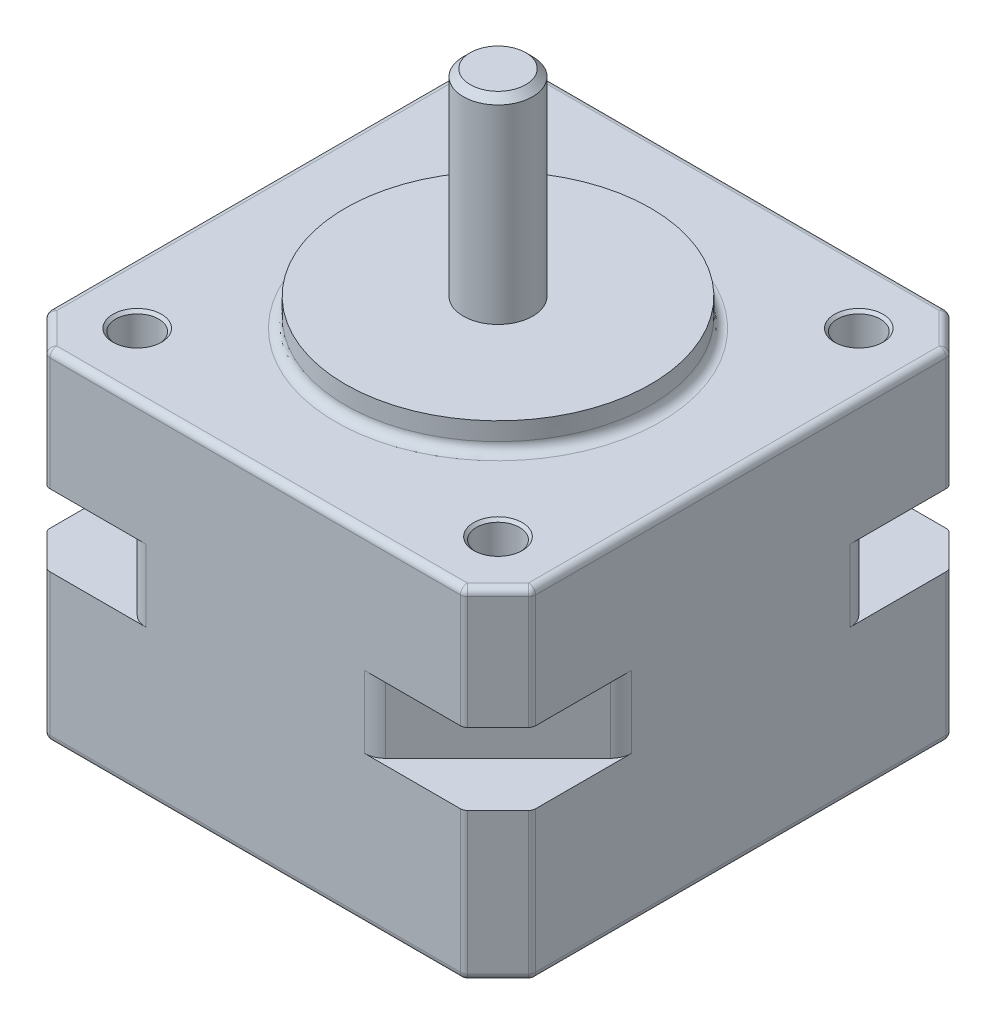
SolidWorks part; units mm, degrees
ref_plane "Front Plane" through (0, 0, 0) normal (0, 0, 1) x (1, 0, 0)
ref_plane "Top Plane" through (0, 0, 0) normal (0, 1, 0) x (1, 0, 0)
ref_plane "Right Plane" through (0, 0, 0) normal (1, 0, 0) x (0, 0, -1)
sketch "Sketch1" plane through (0, 0, 0) normal (0, 1, 0) x (1, 0, 0)
  line L0 (-35, 32.5) -> (-32.5, 35)
  line L1 (-2.5, 0) -> (-32.5, 0)
  line L2 (0, 2.5) -> (0, 32.5)
  line L3 (-2.5, 35) -> (-32.5, 35)
  line L4 (-35, 2.5) -> (-35, 6.85)
  line L5 (0, 32.5) -> (-2.5, 35)
  line L6 (-2.5, 0) -> (0, 2.5)
  line L7 (-32.5, 0) -> (-35, 2.5)
  line L8 (-17.5, 35) -> (-17.5, 0) construction
  line L9 (-42, 21) -> (0, 21) construction
  line L10 (-35, 28.15) -> (-36.65, 28.15)
  line L11 (-36.65, 28.15) -> (-36.65, 6.85)
  line L12 (-36.65, 6.85) -> (-35, 6.85)
  line L13 (-35, 28.15) -> (-35, 32.5)
  circle A0 centre (-17.5, 17.5) radius 4.5
  point P0 (0, 0)
  point P1 (-35, 35)
  point P2 (0, 35)
  point P3 (-35, 0)
  dimension "D11" = 9
  dimension "D1" = 35
  dimension "D2" = 35
  dimension "D3" = 2.5
  dimension "D4" = 45
  dimension "D5" = 2.5
  dimension "D6" = 45
  dimension "D7" = 2.5
  dimension "D8" = 45
  dimension "D9" = 2.5
  dimension "D10" = 45
  dimension "D12" = 1.65
  dimension "D13" = 21.3
extrude "Boss-Extrude1" add sketch "Sketch1" along normal blind 10.7
sketch "Sketch2" plane through (0, 10.7, 0) normal (0, 1, 0) x (1, 0, 0)
  line L1 (-26, 35) -> (-9, 35)
  line L2 (0, 26) -> (0, 9)
  line L3 (-9, 0) -> (-26, 0)
  line L5 (-35, 26) -> (-35, 9)
  line L6 (-26, 35) -> (-35, 26)
  line L7 (-9, 35) -> (0, 26)
  line L8 (0, 9) -> (-9, 0)
  line L9 (-26, 0) -> (-35, 9)
  line L10 (-2.5, 35) -> (-32.5, 35) construction
  point P1 (-35, 35)
  point P5 (0, 35)
  point P6 (0, 0)
  point P8 (-35, 0)
  dimension "D1" = 9
  dimension "D2" = 45
  dimension "D3" = 9
  dimension "D4" = 45
  dimension "D5" = 9
  dimension "D6" = 45
  dimension "D7" = 9
  dimension "D8" = 45
  dimension "D9" = 35
extrude "Boss-Extrude2" add sketch "Sketch2" along normal blind 5.18
sketch "Sketch3" plane through (0, 15.88, 0) normal (0, 1, 0) x (1, 0, 0)
  line L0 (-35, 2.5) -> (-35, 32.5)
  line L1 (-35, 32.5) -> (-32.5, 35)
  line L2 (-32.5, 35) -> (-2.5, 35)
  line L3 (-2.5, 35) -> (0, 32.5)
  line L4 (0, 32.5) -> (0, 2.5)
  line L5 (0, 2.5) -> (-2.5, 0)
  line L6 (-2.5, 0) -> (-32.5, 0)
  line L7 (-32.5, 0) -> (-35, 2.5)
extrude "Boss-Extrude3" add sketch "Sketch3" along normal blind 8.66 contours L1 L2 L3 L4 L5 L6 L7 L0
sketch "Sketch5" plane through (0, 24.54, 0) normal (0, 1, 0) x (1, 0, 0)
  line L0 (-30.5, 4.5) -> (-4.5, 4.5) construction
  line L1 (-4.5, 4.5) -> (-4.5, 30.5) construction
  line L2 (-4.5, 30.5) -> (-30.5, 30.5) construction
  line L3 (-17.5, 4.5) -> (-17.5, -1.0949) construction
  line L4 (-4.5, 17.5) -> (0, 17.5) construction
  line L6 (-35, 2.5) -> (-35, 32.5) construction
  circle A0 centre (-30.5, 4.5) radius 1.55
  circle A1 centre (-4.5, 30.5) radius 1.55
  circle A2 centre (-30.5, 30.5) radius 1.55
  circle A3 centre (-4.5, 4.5) radius 1.55
  dimension "D3" = 3.1
  dimension "D1" = 26
  dimension "D2" = 26
  dimension "D4" = 17.5
  dimension "D5" = 17.5
extrude "Cut-Extrude1" cut sketch "Sketch5" against normal blind 7.5
sketch "Sketch6" plane through (0, 24.54, 0) normal (0, 1, 0) x (1, 0, 0)
  line L0 (-33.75, 33.75) -> (-1.25, 1.25) construction
  line L3 (-35, 32.5) -> (-32.5, 35) construction
  line L4 (0, 2.5) -> (-2.5, 0) construction
  circle A0 centre (-17.5, 17.5) radius 11
  dimension "D1" = 22
extrude "Boss-Extrude4" add sketch "Sketch6" along normal blind 2
sketch "Sketch7" plane through (0, 26.54, 0) normal (0, 1, 0) x (1, 0, 0)
  line L0 (-28.5, 17.5) -> (-6.5, 17.5) construction
  circle A0 centre (-17.5, 17.5) radius 11 construction
  circle A1 centre (-17.5, 17.5) radius 11 construction
  circle A3 centre (-17.5, 17.5) radius 2.5
  dimension "D1" = 5
extrude "Boss-Extrude5" add sketch "Sketch7" along normal blind 14.2
chamfer "Chamfer1" distance 0.2 angle 45 4 edges at (-4.5, 24.54, -2.95) (-4.5, 24.54, -28.95) (-30.5, 24.54, -28.95) (-30.5, 24.54, -2.95)
fillet "Fillet1" radius 0.5 39 edges at (-36.65, 5.35, -28.15) (-36.65, 10.7, -17.5) (-36.65, 5.35, -6.85) (-17.5, 0, -13) (-35.825, 0, -28.15) (-36.65, 0, -17.5) (-35.825, 0, -6.85) (-35, 0, -4.675) (-33.75, 0, -1.25) (-17.5, 0, 0) (-1.25, 0, -1.25) (0, 0, -17.5) (-1.25, 0, -33.75) (-17.5, 0, -35) (-33.75, 0, -33.75) (-2.5, 5.35, -35) (0, 5.35, -32.5) (-32.5, 5.35, -35) (0, 5.35, -2.5) (-2.5, 5.35, 0) (-32.5, 5.35, 0) (-35, 5.35, -2.5) (-35, 20.21, -32.5) (-33.75, 24.54, -33.75) (-32.5, 20.21, -35) (-17.5, 24.54, -35) (-2.5, 20.21, -35) (0, 20.21, -32.5) (0, 24.54, -17.5) (-1.25, 24.54, -33.75) (0, 20.21, -2.5) (-2.5, 20.21, 0) (-35, 20.21, -2.5) (-32.5, 20.21, 0) (-1.25, 24.54, -1.25) (-17.5, 24.54, 0) (-33.75, 24.54, -1.25) (-35, 24.54, -17.5) (-35, 0, -30.325)
fillet "Fillet2" radius 0.7 1 edges at (-17.5, 24.54, -6.5)
chamfer "Chamfer2" distance 0.5 angle 45 1 edges at (-17.5, 40.74, -15)
fillet "Fillet3" radius 1.5 8 edges at (-35, 13.29, -26) (-26, 13.29, -35) (-9, 13.29, -35) (0, 13.29, -26) (0, 13.29, -9) (-9, 13.29, 0) (-26, 13.29, 0) (-35, 13.29, -9)
